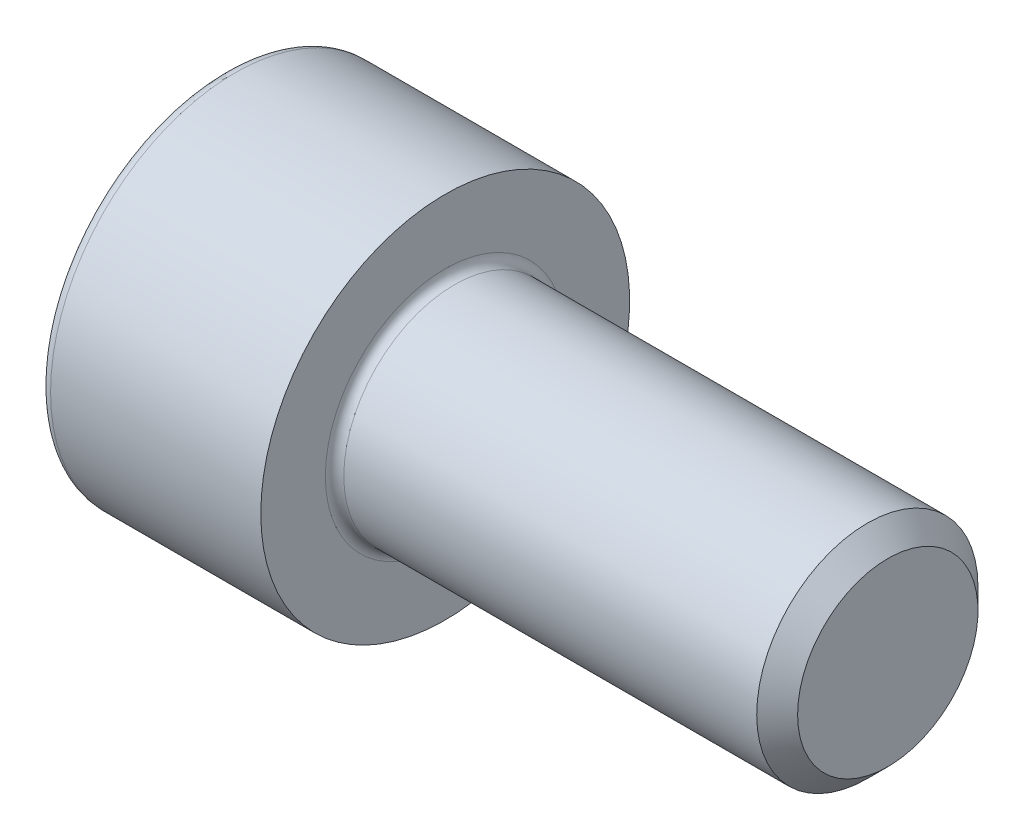
SolidWorks part; units mm, degrees
ref_plane "Front Plane" through (0, 0, 0) normal (0, 0, 1) x (1, 0, 0)
ref_plane "Top Plane" through (0, 0, 0) normal (0, 1, 0) x (1, 0, 0)
ref_plane "Right Plane" through (0, 0, 0) normal (1, 0, 0) x (0, 0, -1)
other "Configuration Table"
sketch "BodySke" plane through (0, 0, 0) normal (0, 0, 1) x (1, 0, 0)
  line L0 (0, 0) -> (5.8492, 0) construction
  line L1 (0, 0) -> (0, 5)
  line L2 (0, 5) -> (6, 5)
  line L3 (6, 5) -> (6, 3)
  line L4 (6, 3) -> (17.4455, 3)
  line L5 (17.4455, 3) -> (18, 2.4455)
  line L6 (18, 2.4455) -> (18, 0)
  line L7 (18, 0) -> (0, 0)
  line L8 (6, 0) -> (6, 0.601) construction
  line L9 (7, 1.5877) -> (7, 0.9267) construction
  dimension "Thread_length" = 12
  dimension "Diameter" = 6
  dimension "Thread_minor" = 4.891
  dimension "Body_chamfer_angle" = 45
  dimension "Length" = 12
  dimension "Head_diameter" = 10
  dimension "Head_length" = 6
  dimension "Advance" = 1
revolve "BaseBody" add sketch "BodySke" angle 360 about L0
cosmetic thread "ThreadCosmetic" [suppressed] parameters "Thread_length"=12, "Thread_minor"=4.891
fillet "Fillet1" radius 0.25 1 edges at (6, 0, 3)
fillet "Fillet2" radius 0.3 1 edges at (0, 0, 5)
sketch "HexSke" plane through (0, 0, 0) normal (1, 0, 0) x (0, 0, -1)
  line L1 (0, 2.8868) -> (-2.5, 1.4434)
  line L2 (-2.5, 1.4434) -> (-2.5, -1.4434)
  line L3 (-2.5, -1.4434) -> (0, -2.8868)
  line L4 (0, -2.8868) -> (2.5, -1.4434)
  line L5 (2.5, -1.4434) -> (2.5, 1.4434)
  line L6 (2.5, 1.4434) -> (0, 2.8868)
  circle A0 centre (0, 0) radius 2.5 construction
  dimension "Hex_size" = 5
extrude "Hex" cut sketch "HexSke" along normal blind 3
sketch "Hex-PreBroachSke" plane through (0, 0, 0) normal (0, 0, 1) x (1, 0, 0)
  line L0 (0, 0) -> (4.7325, 0) construction
  line L1 (0, 4.7) -> (0, -4.7) construction
  line L2 (0, 0) -> (0, 2.5)
  line L3 (0, 2.5) -> (3, 2.5)
  line L4 (3, 2.5) -> (4.4434, 0)
  line L5 (4.4434, 0) -> (0, 0)
  dimension "Hex_depth" = 3
  dimension "D1" = 5
  dimension "Angle" = 60
revolve "Hex-PreBroach" cut sketch "Hex-PreBroachSke" angle 360 about L0
sketch "ThdSchSke" plane through (0, 0, 0) normal (0, 0, 1) x (1, 0, 0)
  line L0 (0, 0) -> (4.4125, 0) construction
  line L1 (0, 4.7) -> (0, -4.7) construction
  line L2 (16.4455, 3.6403) -> (16.4455, 3)
  line L3 (16.4455, 3.6403) -> (17.0858, 3.6403)
  line L4 (17.0858, 3.6403) -> (17.0858, 3)
  line L5 (17.0858, 3) -> (16.7656, 2.4455)
  line L6 (16.7656, 2.4455) -> (16.4455, 3)
  dimension "D1" = 1
revolve "ThreadSchematic" [suppressed] cut sketch "ThdSchSke" angle 360 about L0
pattern_linear "ThdSchPat" [suppressed]
equation "\"Thread_length@ThreadCosmetic\" = \"Thread_length@BodySke\""
equation "\"Thread_minor@ThreadCosmetic\" = \"Thread_minor@BodySke\""
equation "\"Hex_depth@Hex-PreBroachSke\" = \"Hex_length@Hex\""
equation "\"D1@Hex-PreBroachSke\" = \"Hex_size@HexSke\""
equation "\"D1@ThdSchSke\" = \"Advance@BodySke\""
equation "\"Advance@ThdSchPat\" = \"Advance@BodySke\""
equation "\"Tooth_Num@ThdSchPat\" =  int( \"Thread_length@BodySke\" / \"Advance@BodySke\" )  - 1"
